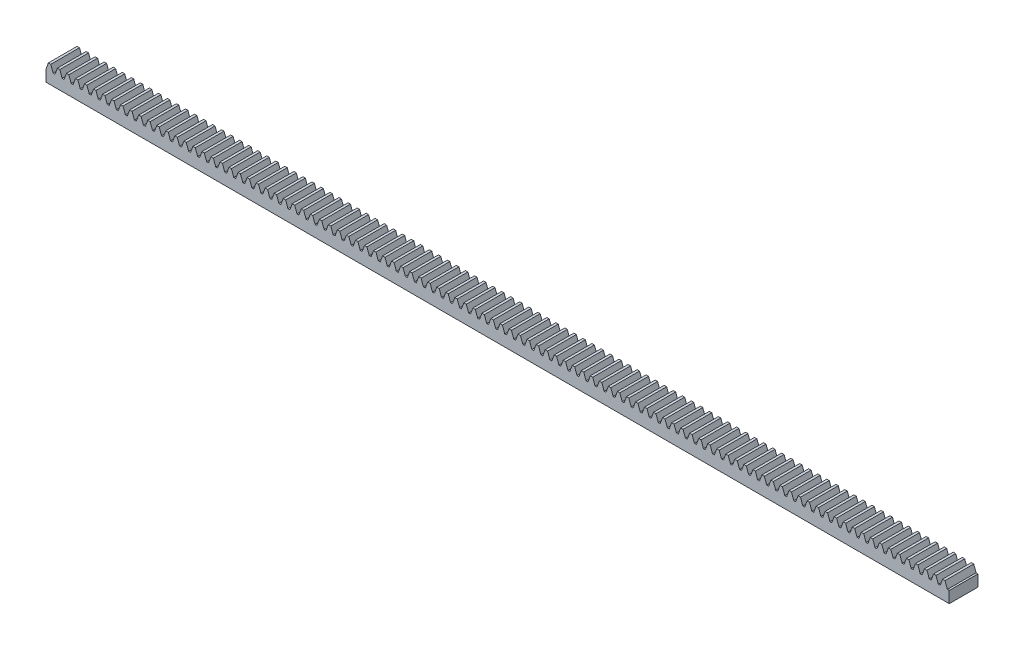
SolidWorks part; units mm, degrees
ref_plane "前视基准面" through (0, 0, 0) normal (0, 0, 1) x (1, 0, 0)
ref_plane "上视基准面" through (0, 0, 0) normal (0, 1, 0) x (1, 0, 0)
ref_plane "右视基准面" through (0, 0, 0) normal (1, 0, 0) x (0, 0, -1)
sketch "草图1" plane through (0, 0, 0) normal (0, 0, 1) x (1, 0, 0)
  line L1 (0, 0) -> (628.3185, 0)
  line L2 (0, 0) -> (0, -7.95)
  line L3 (0, -7.95) -> (628.3185, -7.95)
  line L4 (628.3185, 0) -> (628.3185, -7.95)
  dimension "D1" = 7.95
  dimension "L" = 628.3185
extrude "拉伸1" add sketch "草图1" along normal blind 20
sketch "草图2" plane through (0, 0, 20) normal (0, 0, 1) x (1, 0, 0)
  line L0 (0, 0) -> (1.6379, 4.5)
  line L1 (1.6379, 4.5) -> (3.3236, 4.5)
  line L2 (3.3236, 4.5) -> (4.9614, 0)
  line L3 (628.3185, 0) -> (0, 0) construction
  line L4 (0, 0) -> (4.9614, 0)
  line L5 (0.9099, 2.5) -> (4.0515, 2.5) construction
  dimension "D2" = 70
  dimension "alpha" = 110
  dimension "ha" = 2
  dimension "hf" = 2.5
  dimension "S" = 3.1416
extrude "拉伸2" add sketch "草图2" against normal up to surface (20 mm away) up to face at (314.1593, -3.975, 0)
pattern_linear "阵列(线性)1" count 100 spacing 6.2832 along (1, 0, 0) of "拉伸2"
sketch "草图4" plane through (0, 0, 20) normal (0, 0, 1) x (1, 0, 0)
  line L0 (0.9099, 2.5) -> (4.0515, 2.5)
  line L1 (1.6379, 4.5) -> (0, 0) construction
  line L2 (4.9614, 0) -> (3.3236, 4.5) construction
  line L3 (3.3236, 4.5) -> (1.6379, 4.5) construction
  dimension "D1" = 2
equation "\"d\"=\"S@草图2\" * 2"
equation "\"z\"= int(  \"L@草图1\" / (  \"S@草图2\" * 2 ) + 0.5 )"
